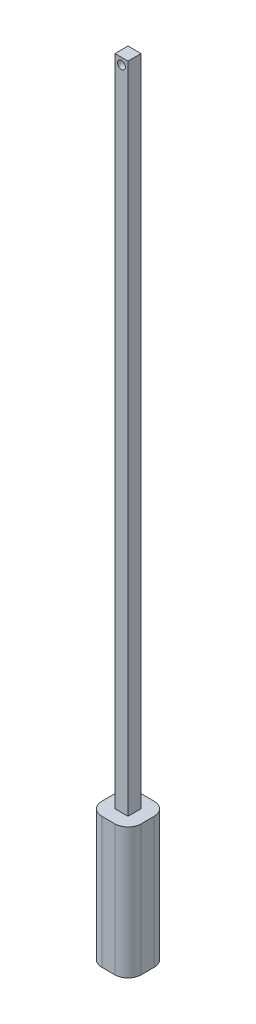
SolidWorks part; units mm, degrees
ref_plane "Front Plane" through (0, 0, 0) normal (0, 0, 1) x (1, 0, 0)
ref_plane "Top Plane" through (0, 0, 0) normal (0, 1, 0) x (1, 0, 0)
ref_plane "Right Plane" through (0, 0, 0) normal (1, 0, 0) x (0, 0, -1)
sketch "Sketch1" plane through (0, 0, 0) normal (0, 0, 1) x (1, 0, 0)
  line L1 (-5, 5) -> (5, 5)
  line L2 (-5, 5) -> (-5, -495)
  line L3 (-5, -495) -> (5, -495)
  line L4 (5, 5) -> (5, -495)
  circle A0 centre (0, 0) radius 3
  dimension "D1" = 6
  dimension "D2" = 5
  dimension "D3" = 10
  dimension "D4" = 5
  dimension "D5" = 500
extrude "Boss-Extrude1" add sketch "Sketch1" along normal blind 10
sketch "Sketch2" plane through (0, -495, 0) normal (0, -1, 0) x (1, 0, 0)
  line L0 (5, 10) -> (5, 0) construction
  line L1 (-15, 20) -> (15, 20)
  line L2 (-15, 20) -> (-15, -10)
  line L3 (-15, -10) -> (15, -10)
  line L4 (15, 20) -> (15, -10)
  line L5 (-15, 20) -> (15, -10) construction
  line L6 (-15, -10) -> (15, 20) construction
  line L8 (-5, 0) -> (5, 0) construction
  point P0 (0, 5)
  dimension "D1" = 30
  dimension "D2" = 30
  dimension "D3" = 5
  dimension "D4" = 5
extrude "Boss-Extrude2" add sketch "Sketch2" along normal blind 100
fillet "Fillet1" radius 10 4 edges at (-15, -545, -10) (15, -545, -10) (15, -545, 20) (-15, -545, 20)
